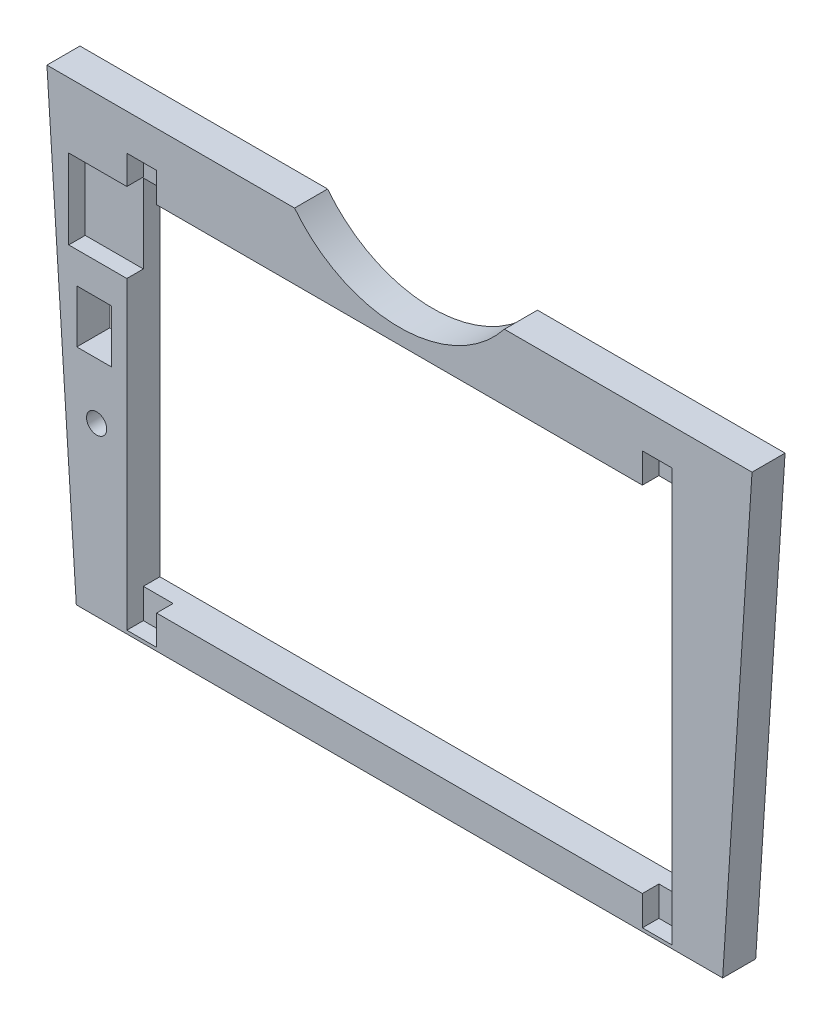
SolidWorks part; units mm, degrees
ref_plane "Front Plane" through (0, 0, 0) normal (0, 0, 1) x (1, 0, 0)
ref_plane "Top Plane" through (0, 0, 0) normal (0, 1, 0) x (1, 0, 0)
ref_plane "Right Plane" through (0, 0, 0) normal (1, 0, 0) x (0, 0, -1)
sketch "Sketch1" plane through (0, 0, 0) normal (0, 0, 1) x (1, 0, 0)
  line L0 (-106.68, 73.5) -> (-31.75, 73.5)
  line L1 (-82.5, 53.5) -> (82.5, 53.5)
  line L2 (-82.5, 53.5) -> (-82.5, -53.5)
  line L3 (-82.5, -53.5) -> (82.5, -53.5)
  line L4 (82.5, 53.5) -> (82.5, -53.5)
  line L5 (-97.79, -63.5) -> (97.79, -63.5)
  line L6 (-106.68, 73.5) -> (-97.79, -63.5)
  line L7 (106.68, 73.5) -> (97.79, -63.5)
  line L8 (31.75, 73.5) -> (106.68, 73.5)
  arc A1 (-31.75, 73.5) -> (31.75, 73.5) centre (0, 98.4741) ccw
  dimension "D1" = 165
  dimension "D2" = 107
  dimension "D3" = 82.5
  dimension "D4" = 53.5
  dimension "D5" = 195.58
  dimension "D6" = 213.36
  dimension "D7" = 106.68
  dimension "D8" = 97.79
  dimension "D9" = 10
  dimension "D10" = 20
  dimension "D14" = 63.5
  dimension "D15" = 31.75
extrude "Boss-Extrude1" add sketch "Sketch1" along normal blind 10
sketch "Sketch2" plane through (0, 0, 10) normal (0, 0, 1) x (1, 0, 0)
  line L1 (82.5, 53.5) -> (73.5, 53.5)
  line L2 (82.5, 53.5) -> (82.5, 62.5)
  line L3 (82.5, 62.5) -> (73.5, 62.5)
  line L4 (73.5, 53.5) -> (73.5, 62.5)
  line L5 (-82.5, 53.5) -> (-73.5, 53.5)
  line L6 (-82.5, 53.5) -> (-82.5, 62.5)
  line L7 (-82.5, 62.5) -> (-73.5, 62.5)
  line L8 (-73.5, 53.5) -> (-73.5, 62.5)
  dimension "D1" = 9
  dimension "D2" = 9
  dimension "D3" = 9
  dimension "D4" = 9
extrude "Cut-Extrude1" cut sketch "Sketch2" against normal blind 5
sketch "Sketch3" plane through (0, 0, 10) normal (0, 0, 1) x (1, 0, 0)
  line L0 (-82.5, 62.5) -> (-82.5, -53.5) construction
  line L1 (-82.5, 53.7645) -> (-100.0864, 53.7645)
  line L2 (-82.5, 53.7645) -> (-82.5, 29.6689)
  line L3 (-82.5, 29.6689) -> (-100.0864, 29.6689)
  line L4 (-100.0864, 53.7645) -> (-100.0864, 29.6689)
extrude "Cut-Extrude2" cut sketch "Sketch3" against normal blind 5
sketch "Sketch6" plane through (0, 0, 0) normal (0, 0, -1) x (-1, 0, 0)
  line L1 (87.1531, 20.158) -> (97.6531, 20.158)
  line L2 (87.1531, 20.158) -> (87.1531, 4.158)
  line L3 (87.1531, 4.158) -> (97.6531, 4.158)
  line L4 (97.6531, 20.158) -> (97.6531, 4.158)
  dimension "D1" = 16
  dimension "D2" = 10.5
extrude "Cut-Extrude3" cut sketch "Sketch6" against normal through all
sketch "Sketch8" plane through (0, 0, 0) normal (0, 0, -1) x (-1, 0, 0)
  circle A0 centre (91.642, -12.8754) radius 3.05
  point P2 (91.642, -12.8754)
  dimension "D1" = 6.1
extrude "Cut-Extrude4" cut sketch "Sketch8" against normal through all
sketch "Sketch9" plane through (0, 0, 10) normal (0, 0, 1) x (1, 0, 0)
  line L1 (82.5, -53.5) -> (73.5, -53.5)
  line L2 (82.5, -53.5) -> (82.5, -62.5)
  line L3 (82.5, -62.5) -> (73.5, -62.5)
  line L4 (73.5, -53.5) -> (73.5, -62.5)
  line L5 (-82.5, -53.5) -> (-73.5, -53.5)
  line L6 (-82.5, -53.5) -> (-82.5, -62.5)
  line L7 (-82.5, -62.5) -> (-73.5, -62.5)
  line L8 (-73.5, -53.5) -> (-73.5, -62.5)
  dimension "D1" = 9
  dimension "D2" = 9
  dimension "D3" = 9
  dimension "D4" = 9
extrude "Cut-Extrude5" cut sketch "Sketch9" against normal blind 5
equation "\"D3@Sketch1\"=\"D1@Sketch1\"/2"
equation "\"D4@Sketch1\"=\"D2@Sketch1\"/2"
equation "\"D7@Sketch1\"=\"D6@Sketch1\"/2"
equation "\"D8@Sketch1\"=\"D5@Sketch1\"/2"
equation "\"D15@Sketch1\"=\"D14@Sketch1\"/2"
